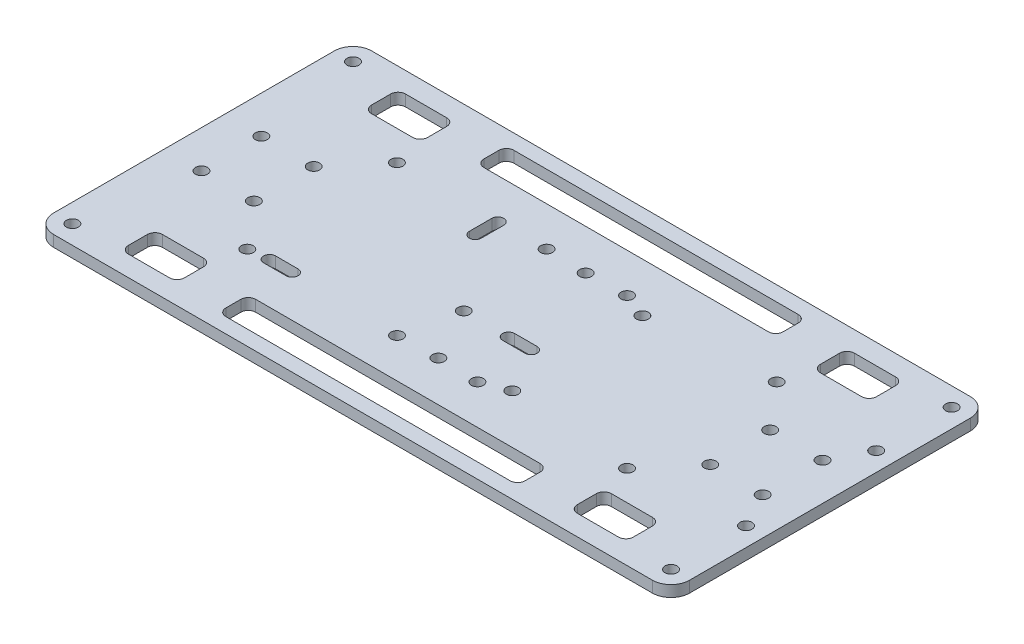
SolidWorks part; units mm, degrees
ref_plane "Front Plane" through (0, 0, 0) normal (0, 0, 1) x (1, 0, 0)
ref_plane "Top Plane" through (0, 0, 0) normal (0, 1, 0) x (1, 0, 0)
ref_plane "Right Plane" through (0, 0, 0) normal (1, 0, 0) x (0, 0, -1)
sketch "Sketch1" plane through (0, 0, 0) normal (0, 1, 0) x (1, 0, 0)
  line L0 (0, 42.5) -> (0, -42.5) construction
  line L1 (-80, 42.5) -> (80, 42.5)
  line L2 (-85, 37.5) -> (-85, -37.5)
  line L3 (-80, -42.5) -> (80, -42.5)
  line L4 (85, 37.5) -> (85, -37.5)
  line L5 (-85, 42.5) -> (85, -42.5) construction
  line L6 (-85, -42.5) -> (85, 42.5) construction
  line L7 (-85, 0) -> (75, 0) construction
  line L8 (-68, 42.5) -> (-68, -42.5) construction
  line L9 (-40, -30.5) -> (40, -38.5) construction
  line L10 (-38, 38.5) -> (38, 38.5)
  line L11 (-40, 36.5) -> (-40, 32.5)
  line L12 (-38, 30.5) -> (38, 30.5)
  line L13 (40, 36.5) -> (40, 32.5)
  line L14 (-40, 38.5) -> (40, 30.5) construction
  line L15 (-40, 30.5) -> (40, 38.5) construction
  line L16 (-40, -38.5) -> (40, -30.5) construction
  line L17 (40, -36.5) -> (40, -32.5)
  line L18 (-38, -30.5) -> (38, -30.5)
  line L19 (-40, -36.5) -> (-40, -32.5)
  line L20 (-38, -38.5) -> (38, -38.5)
  line L21 (-30.75, 25) -> (-30.75, -25) construction
  line L22 (-56, 25) -> (-5.5, 25) construction
  line L23 (-56, 25) -> (-56, -25) construction
  line L24 (-56, -25) -> (-5.5, -25) construction
  line L25 (-5.5, 25) -> (-5.5, -25) construction
  line L26 (-56, 25) -> (-5.5, -25) construction
  line L27 (-56, -25) -> (-5.5, 25) construction
  arc A0 (80, 42.5) -> (85, 37.5) centre (80, 37.5) cw
  arc A1 (85, -37.5) -> (80, -42.5) centre (80, -37.5) cw
  arc A2 (-85, -37.5) -> (-80, -42.5) centre (-80, -37.5) ccw
  arc A3 (-80, 42.5) -> (-85, 37.5) centre (-80, 37.5) ccw
  circle A4 centre (-80, 37.5) radius 1.6
  circle A5 centre (80, 37.5) radius 1.6
  circle A6 centre (-80, -37.5) radius 1.6
  circle A7 centre (80, -37.5) radius 1.6
  circle A8 centre (-75, 8) radius 1.6
  circle A9 centre (-75, -8) radius 1.6
  circle A10 centre (-61, -8) radius 1.6
  circle A11 centre (-61, 8) radius 1.6
  circle A12 centre (61, -8) radius 1.6
  circle A13 centre (75, -8) radius 1.6
  circle A14 centre (61, 8) radius 1.6
  circle A15 centre (75, 8) radius 1.6
  arc A16 (-40, 36.5) -> (-38, 38.5) centre (-38, 36.5) cw
  arc A17 (-38, 30.5) -> (-40, 32.5) centre (-38, 32.5) cw
  arc A18 (40, 36.5) -> (38, 38.5) centre (38, 36.5) ccw
  arc A19 (38, 30.5) -> (40, 32.5) centre (38, 32.5) ccw
  arc A20 (38, -30.5) -> (40, -32.5) centre (38, -32.5) cw
  arc A21 (40, -36.5) -> (38, -38.5) centre (38, -36.5) cw
  arc A22 (-38, -30.5) -> (-40, -32.5) centre (-38, -32.5) ccw
  arc A23 (-40, -36.5) -> (-38, -38.5) centre (-38, -36.5) ccw
  circle A24 centre (-50.75, 20) radius 1.6
  circle A25 centre (-10.75, 20) radius 1.6
  circle A26 centre (-10.75, -20) radius 1.6
  circle A27 centre (-50.75, -20) radius 1.6
  circle A28 centre (50.75, -20) radius 1.6
  circle A29 centre (10.75, -20) radius 1.6
  circle A30 centre (10.75, 20) radius 1.6
  circle A31 centre (50.75, 20) radius 1.6
  circle A32 centre (0, 19.68) radius 1.6
  circle A33 centre (0, -19.68) radius 1.6
  point P0 (0, 0)
  point P44 (0, 34.5)
  point P77 (0, -34.5)
  point P78 (-30.75, 0)
  dimension "D3" = 5
  dimension "D4" = 5
  dimension "D5" = 5
  dimension "D6" = 5
  dimension "D7" = 3.2
  dimension "D8" = 3.2
  dimension "D9" = 3.2
  dimension "D10" = 3.2
  dimension "D11" = 3.2
  dimension "D18" = 2
  dimension "D19" = 2
  dimension "D20" = 2
  dimension "D21" = 2
  dimension "D25" = 3.2
  dimension "D28" = 3.2
  dimension "D1" = 170
  dimension "D2" = 85
  dimension "D12" = 10
  dimension "D13" = 8
  dimension "D14" = 7
  dimension "D15" = 80
  dimension "D16" = 8
  dimension "D17" = 8
  dimension "D22" = 50.5
  dimension "D23" = 50
  dimension "D24" = 5
  dimension "D26" = 20
  dimension "D27" = 20
  dimension "D29" = 19.68
extrude "Boss-Extrude1" add sketch "Sketch1" along normal blind 3
sketch "Sketch2" plane through (0, 3, 0) normal (0, 1, 0) x (1, 0, 0)
  line L0 (-85, 0) -> (85, 0) construction
  line L1 (-85, 37.5) -> (-85, -37.5) construction
  line L2 (85, -37.5) -> (85, 37.5) construction
  line L3 (0, 42.5) -> (0, -42.5) construction
  line L4 (80, 42.5) -> (-80, 42.5) construction
  line L5 (-80, -42.5) -> (80, -42.5) construction
  line L6 (52.5, -27.95) -> (67.5, -37.05) construction
  line L7 (-40.5, 30.3) -> (40.5, 30.3) construction
  line L8 (-40.5, 30.3) -> (-40.5, -30.3) construction
  line L9 (-40.5, -30.3) -> (40.5, -30.3) construction
  line L10 (40.5, 30.3) -> (40.5, -30.3) construction
  line L11 (-40.5, 30.3) -> (40.5, -30.3) construction
  line L12 (-40.5, -30.3) -> (40.5, 30.3) construction
  line L13 (54.5, 37.05) -> (65.5, 37.05)
  line L14 (52.5, 35.05) -> (52.5, 29.95)
  line L15 (54.5, 27.95) -> (65.5, 27.95)
  line L16 (67.5, 35.05) -> (67.5, 29.95)
  line L17 (52.5, 37.05) -> (67.5, 27.95) construction
  line L18 (52.5, 27.95) -> (67.5, 37.05) construction
  line L19 (52.5, -37.05) -> (67.5, -27.95) construction
  line L20 (67.5, -35.05) -> (67.5, -29.95)
  line L21 (54.5, -27.95) -> (65.5, -27.95)
  line L22 (52.5, -35.05) -> (52.5, -29.95)
  line L23 (54.5, -37.05) -> (65.5, -37.05)
  line L24 (-52.5, -37.05) -> (-67.5, -27.95) construction
  line L25 (-52.5, -27.95) -> (-67.5, -37.05) construction
  line L26 (-54.5, -37.05) -> (-65.5, -37.05)
  line L27 (-52.5, -35.05) -> (-52.5, -29.95)
  line L28 (-54.5, -27.95) -> (-65.5, -27.95)
  line L29 (-67.5, -35.05) -> (-67.5, -29.95)
  line L30 (-52.5, 27.95) -> (-67.5, 37.05) construction
  line L31 (-52.5, 37.05) -> (-67.5, 27.95) construction
  line L32 (-67.5, 35.05) -> (-67.5, 29.95)
  line L33 (-54.5, 27.95) -> (-65.5, 27.95)
  line L34 (-52.5, 35.05) -> (-52.5, 29.95)
  line L35 (-54.5, 37.05) -> (-65.5, 37.05)
  arc A0 (52.5, 35.05) -> (54.5, 37.05) centre (54.5, 35.05) cw
  arc A1 (54.5, 27.95) -> (52.5, 29.95) centre (54.5, 29.95) cw
  arc A2 (67.5, 29.95) -> (65.5, 27.95) centre (65.5, 29.95) cw
  arc A3 (65.5, 37.05) -> (67.5, 35.05) centre (65.5, 35.05) cw
  arc A4 (65.5, -37.05) -> (67.5, -35.05) centre (65.5, -35.05) ccw
  arc A5 (67.5, -29.95) -> (65.5, -27.95) centre (65.5, -29.95) ccw
  arc A6 (54.5, -27.95) -> (52.5, -29.95) centre (54.5, -29.95) ccw
  arc A7 (52.5, -35.05) -> (54.5, -37.05) centre (54.5, -35.05) ccw
  arc A8 (-52.5, -35.05) -> (-54.5, -37.05) centre (-54.5, -35.05) cw
  arc A9 (-54.5, -27.95) -> (-52.5, -29.95) centre (-54.5, -29.95) cw
  arc A10 (-67.5, -29.95) -> (-65.5, -27.95) centre (-65.5, -29.95) cw
  arc A11 (-65.5, -37.05) -> (-67.5, -35.05) centre (-65.5, -35.05) cw
  arc A12 (-65.5, 37.05) -> (-67.5, 35.05) centre (-65.5, 35.05) ccw
  arc A13 (-67.5, 29.95) -> (-65.5, 27.95) centre (-65.5, 29.95) ccw
  arc A14 (-54.5, 27.95) -> (-52.5, 29.95) centre (-54.5, 29.95) ccw
  arc A15 (-52.5, 35.05) -> (-54.5, 37.05) centre (-54.5, 35.05) ccw
  point P12 (0, 0)
  point P18 (60, 32.5)
  point P51 (60, -32.5)
  point P68 (-60, -32.5)
  point P85 (-60, 32.5)
  dimension "D7" = 2
  dimension "D8" = 2
  dimension "D9" = 2
  dimension "D10" = 2
  dimension "D1" = 81
  dimension "D2" = 60.6
  dimension "D3" = 15
  dimension "D4" = 9.1
  dimension "D5" = 60
  dimension "D6" = 10
extrude "Cut-Extrude1" cut sketch "Sketch2" against normal blind 3
sketch "Sketch3" plane through (0, 3, 0) normal (0, 1, 0) x (1, 0, 0)
  line L0 (0, 42.5) -> (0, -42.5) construction
  line L1 (80, 42.5) -> (-80, 42.5) construction
  line L2 (-80, -42.5) -> (80, -42.5) construction
  line L3 (-85, 0) -> (85, 0) construction
  line L4 (-85, 37.5) -> (-85, -37.5) construction
  line L5 (85, -37.5) -> (85, 37.5) construction
  line L6 (48.705, 20.445) -> (48.705, -20.445) construction
  line L7 (-10.1, 8) -> (10.1, 8) construction
  line L8 (-10.1, 8) -> (-10.1, -8) construction
  line L9 (-10.1, -8) -> (10.1, -8) construction
  line L10 (10.1, 8) -> (10.1, -8) construction
  line L11 (-10.1, 8) -> (10.1, -8) construction
  line L12 (-10.1, -8) -> (10.1, 8) construction
  line L13 (17.41, 20.445) -> (80, 20.445) construction
  line L14 (14.41, 17.445) -> (14.41, -17.445) construction
  line L15 (17.41, -20.445) -> (80, -20.445) construction
  line L16 (83, 17.445) -> (83, -17.445) construction
  line L17 (14.41, 20.445) -> (83, -20.445) construction
  line L18 (14.41, -20.445) -> (83, 20.445) construction
  line L19 (4.5, -5.4) -> (10.5, -5.4) construction
  line L20 (-45, 27) -> (-21, 27) construction
  line L21 (-45, 27) -> (-45, -27) construction
  line L22 (-45, -27) -> (-21, -27) construction
  line L23 (-21, 27) -> (-21, -27) construction
  line L24 (-45, 27) -> (-21, -27) construction
  line L25 (-45, -27) -> (-21, 27) construction
  line L26 (4.5, -3.8) -> (10.5, -3.8)
  line L27 (4.5, -7) -> (10.5, -7)
  line L28 (-23.6, 13.8) -> (-23.6, 19.8) construction
  line L29 (-25.2, 13.8) -> (-25.2, 19.8)
  line L30 (-22, 13.8) -> (-22, 19.8)
  line L31 (-39.4, -19.4) -> (-45.4, -19.4) construction
  line L32 (-39.4, -21) -> (-45.4, -21)
  line L33 (-39.4, -17.8) -> (-45.4, -17.8)
  circle A0 centre (-7.5, -5.4) radius 1.6
  circle A1 centre (7.5, -5.4) radius 1.6 construction
  arc A2 (14.41, 17.445) -> (17.41, 20.445) centre (17.41, 17.445) cw construction
  arc A3 (17.41, -20.445) -> (14.41, -17.445) centre (17.41, -17.445) cw construction
  arc A4 (83, -17.445) -> (80, -20.445) centre (80, -17.445) cw construction
  arc A5 (80, 20.445) -> (83, 17.445) centre (80, 17.445) cw construction
  circle A6 centre (17.465, 17.395) radius 1.6
  circle A7 centre (17.465, -17.395) radius 1.6
  circle A8 centre (79.945, -17.395) radius 1.6
  circle A9 centre (79.945, 17.395) radius 1.6
  circle A10 centre (-23.6, 16.8) radius 1.6 construction
  circle A11 centre (-42.4, -19.4) radius 1.6 construction
  arc A12 (4.5, -3.8) -> (4.5, -7) centre (4.5, -5.4) ccw
  arc A13 (10.5, -7) -> (10.5, -3.8) centre (10.5, -5.4) ccw
  arc A14 (-25.2, 13.8) -> (-22, 13.8) centre (-23.6, 13.8) ccw
  arc A15 (-22, 19.8) -> (-25.2, 19.8) centre (-23.6, 19.8) ccw
  arc A16 (-39.4, -21) -> (-39.4, -17.8) centre (-39.4, -19.4) ccw
  arc A17 (-45.4, -17.8) -> (-45.4, -21) centre (-45.4, -19.4) ccw
  point P12 (0, 0)
  point P23 (48.705, 0)
  point P49 (-33, 0)
  point P60 (7.5, -5.4)
  point P67 (-23.6, 16.8)
  point P74 (-42.4, -19.4)
  dimension "D3" = 3.2
  dimension "D9" = 3
  dimension "D10" = 3
  dimension "D11" = 3
  dimension "D12" = 3
  dimension "D13" = 3.2
  dimension "D19" = 3.2
  dimension "D24" = 3.2
  dimension "D27" = 6
  dimension "D1" = 20.2
  dimension "D2" = 16
  dimension "D4" = 7.5
  dimension "D5" = 2.6
  dimension "D6" = 40.89
  dimension "D7" = 68.59
  dimension "D8" = 2
  dimension "D14" = 31.24
  dimension "D15" = 17.395
  dimension "D16" = 54
  dimension "D17" = 24
  dimension "D18" = 52
  dimension "D20" = 10.2
  dimension "D21" = 7.6
  dimension "D22" = 2.6
  dimension "D23" = 2.6
  dimension "D25" = 6
  dimension "D26" = 3.2
  dimension "D28" = 3.2
  dimension "D29" = 6
  dimension "D30" = 3.2
extrude "Cut-Extrude2" cut sketch "Sketch3" against normal blind 3
